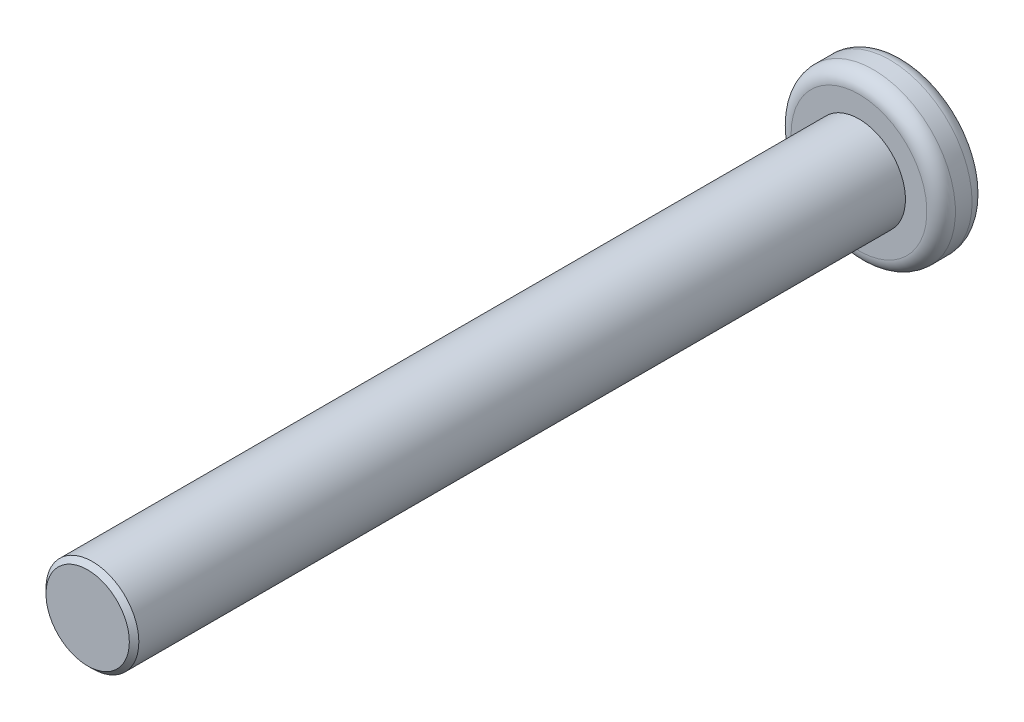
SolidWorks part; units mm, degrees
ref_plane "Plan de face" through (0, 0, 0) normal (0, 0, 1) x (1, 0, 0)
ref_plane "Plan de dessus" through (0, 0, 0) normal (0, 1, 0) x (1, 0, 0)
ref_plane "Plan de droite" through (0, 0, 0) normal (1, 0, 0) x (0, 0, -1)
sketch "Esquisse1" plane through (0, 0, 0) normal (0, 0, 1) x (1, 0, 0)
  circle A0 centre (0, 0) radius 0.975
  dimension "D1" = 1.95
extrude "Boss.-Extru.1" add sketch "Esquisse1" along normal blind 17.15
sketch "Esquisse2" plane through (0, 0, 0) normal (0, 0, -1) x (-1, 0, 0)
  circle A0 centre (0, 0) radius 1.725
  dimension "D1" = 3.45
extrude "Boss.-Extru.2" add sketch "Esquisse2" against normal blind 0.95
fillet "Congé1" radius 0.3 2 edges at (-1.725, 0, 0) (-1.725, 0, 0.95)
chamfer "Chanfrein1" distance 0.1 angle 45 1 edges at (0.975, 0, 17.15)
scale "Scale1" scale about centroid uniform scaling yes scale factor 6.5
